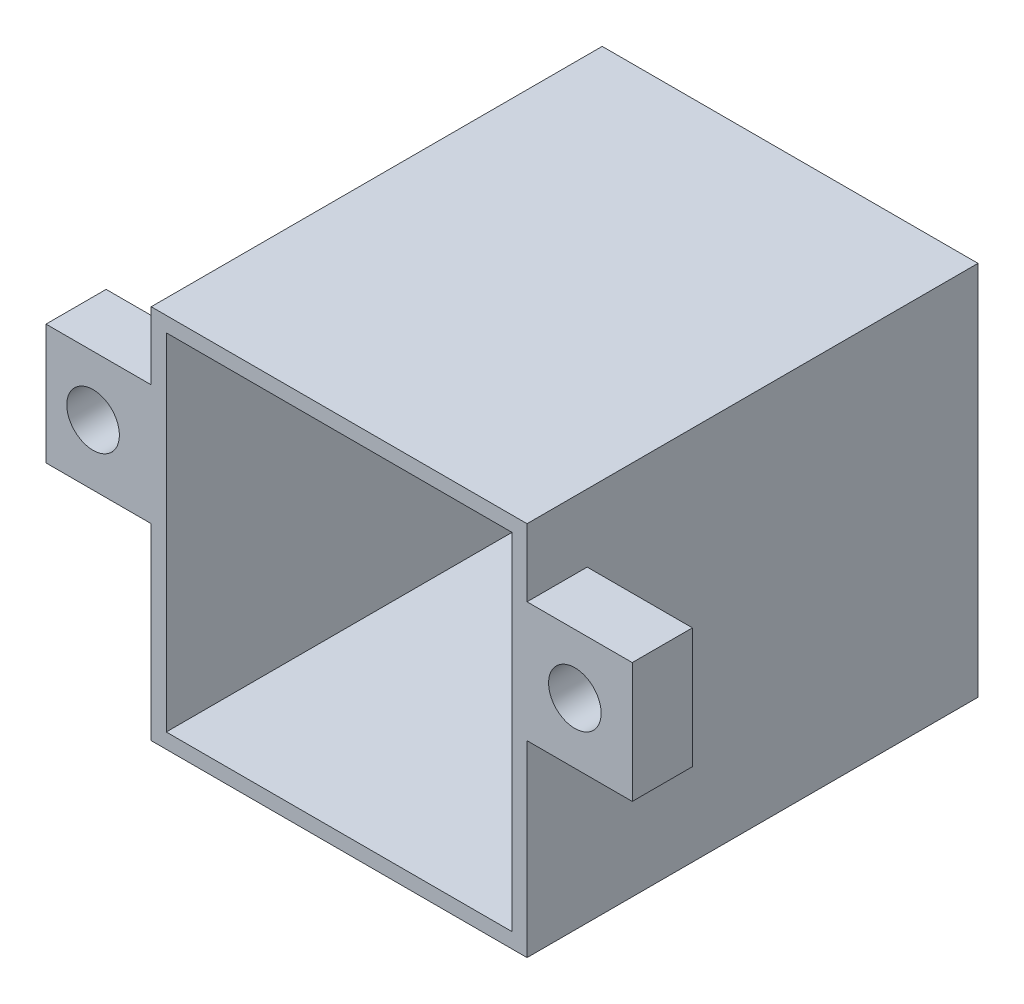
SolidWorks part; units mm, degrees
ref_plane "Front Plane" through (0, 0, 0) normal (0, 0, 1) x (1, 0, 0)
ref_plane "Top Plane" through (0, 0, 0) normal (0, 1, 0) x (1, 0, 0)
ref_plane "Right Plane" through (0, 0, 0) normal (1, 0, 0) x (0, 0, -1)
sketch "Sketch1" plane through (0, 0, 0) normal (0, 0, 1) x (1, 0, 0)
  line L1 (-12.5, -12.5) -> (12.5, -12.5)
  line L2 (-12.5, -12.5) -> (-12.5, 12.5)
  line L3 (-12.5, 12.5) -> (12.5, 12.5)
  line L4 (12.5, -12.5) -> (12.5, 12.5)
  line L5 (-12.5, -12.5) -> (12.5, 12.5) construction
  line L6 (-12.5, 12.5) -> (12.5, -12.5) construction
  dimension "D2" = 25
  dimension "D3" = 25
extrude "Boss-Extrude2" add sketch "Sketch1" along normal blind 30
shell "Shell3" thickness 1
sketch "Sketch4" plane through (0, 0, 0) normal (0, 0, -1) x (-1, 0, 0)
  circle A0 centre (0, 0) radius 5.25
  dimension "D1" = 10.5
extrude "Cut-Extrude2" cut sketch "Sketch4" against normal blind 25
sketch "Sketch5" plane through (0, 0, 30) normal (0, 0, 1) x (1, 0, 0)
  line L0 (12.5, -12.5) -> (12.5, 12.5) construction
  line L1 (12.5, 0) -> (19.5, 0)
  line L2 (12.5, 0) -> (12.5, 8)
  line L3 (12.5, 8) -> (19.5, 8)
  line L4 (19.5, 0) -> (19.5, 8)
  line L5 (-12.5, 12.5) -> (-12.5, -12.5) construction
  line L6 (-12.5, 0) -> (-19.5, 0)
  line L7 (-12.5, 0) -> (-12.5, 8)
  line L8 (-12.5, 8) -> (-19.5, 8)
  line L9 (-19.5, 0) -> (-19.5, 8)
  dimension "D1" = 7
  dimension "D2" = 8
  dimension "D3" = 7
  dimension "D4" = 8
extrude "Boss-Extrude3" add sketch "Sketch5" against normal blind 4
sketch "Sketch6" plane through (0, 0, 30) normal (0, 0, 1) x (1, 0, 0)
  circle A0 centre (15.6821, 4.0433) radius 1.75
  circle A1 centre (-16.3676, 4.0433) radius 1.75
  dimension "D1" = 3.5
  dimension "D2" = 3.5
extrude "Cut-Extrude3" cut sketch "Sketch6" against normal blind 10
